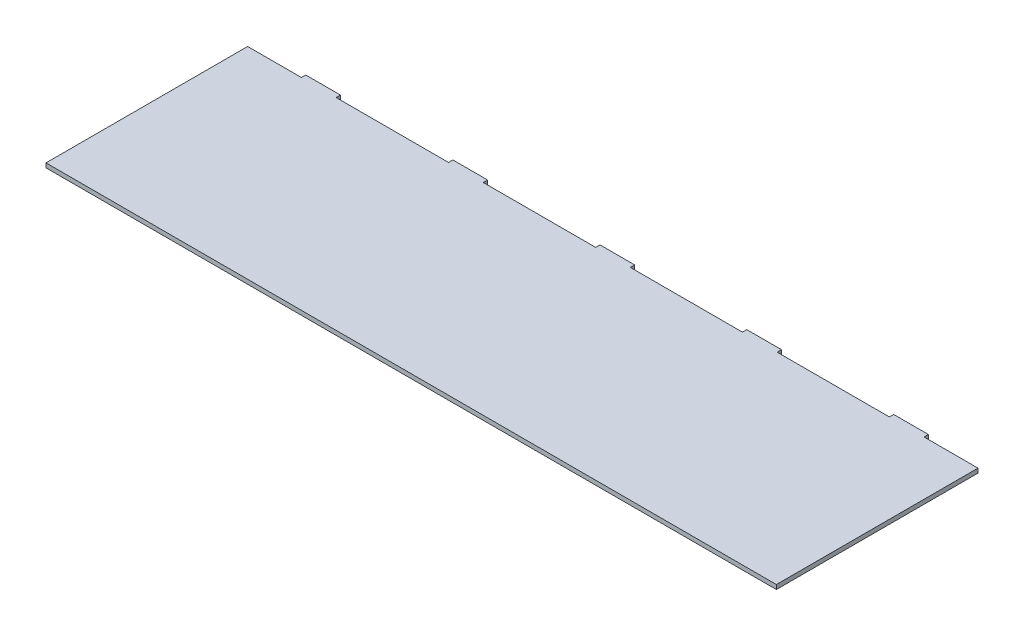
SolidWorks part; units mm, degrees
material "6061-T6 (SS)"
ref_plane "X-Y Datum" through (0, 0, 0) normal (0, 0, 1) x (1, 0, 0)
ref_plane "X-Z Datum" through (0, 0, 0) normal (0, 1, 0) x (1, 0, 0)
ref_plane "Y-Z Datum" through (0, 0, 0) normal (1, 0, 0) x (0, 0, -1)
sketch "Sketch1" plane through (0, 0, 0) normal (0, 1, 0) x (1, 0, 0)
  line L1 (0, 0) -> (534.9977, 0)
  line L2 (0, 0) -> (0, 147.6985)
  line L3 (0, 147.6985) -> (534.9977, 147.6985)
  line L4 (534.9977, 0) -> (534.9977, 147.6985)
extrude "Boss-Extrude1" add sketch "Sketch1" along normal blind 3.175
sketch "Sketch2" plane through (0, 0, -147.6985) normal (0, 0, -1) x (-1, 0, 0)
  line L0 (0, 0) -> (0, 3.175) construction
  line L1 (0, 0) -> (-534.9977, 0) construction
  line L2 (-534.9977, 0) -> (-534.9977, 3.175) construction
  line L3 (0, 3.175) -> (-534.9977, 3.175) construction
  line L4 (-495.4714, 0) -> (-495.4714, 3.175)
  line L5 (-495.4714, 0) -> (-470.0714, 0)
  line L6 (-470.0714, 0) -> (-470.0714, 3.175)
  line L7 (-495.4714, 3.175) -> (-470.0714, 3.175)
  line L8 (-387.844, 0) -> (-387.844, 3.175)
  line L9 (-387.844, 0) -> (-362.444, 0)
  line L10 (-362.444, 0) -> (-362.444, 3.175)
  line L11 (-387.844, 3.175) -> (-362.444, 3.175)
  line L12 (-280.3653, 0) -> (-280.3653, 3.175)
  line L13 (-280.3653, 0) -> (-254.9653, 0)
  line L14 (-254.9653, 0) -> (-254.9653, 3.175)
  line L15 (-280.3653, 3.175) -> (-254.9653, 3.175)
  line L16 (-172.589, 0) -> (-172.589, 3.175)
  line L17 (-172.589, 0) -> (-147.189, 0)
  line L18 (-147.189, 0) -> (-147.189, 3.175)
  line L19 (-172.589, 3.175) -> (-147.189, 3.175)
  line L20 (-64.7981, 0) -> (-64.7981, 3.175)
  line L21 (-64.7981, 0) -> (-39.3981, 0)
  line L22 (-39.3981, 0) -> (-39.3981, 3.175)
  line L23 (-64.7981, 3.175) -> (-39.3981, 3.175)
extrude "Boss-Extrude2" add sketch "Sketch2" along normal blind 3.175
